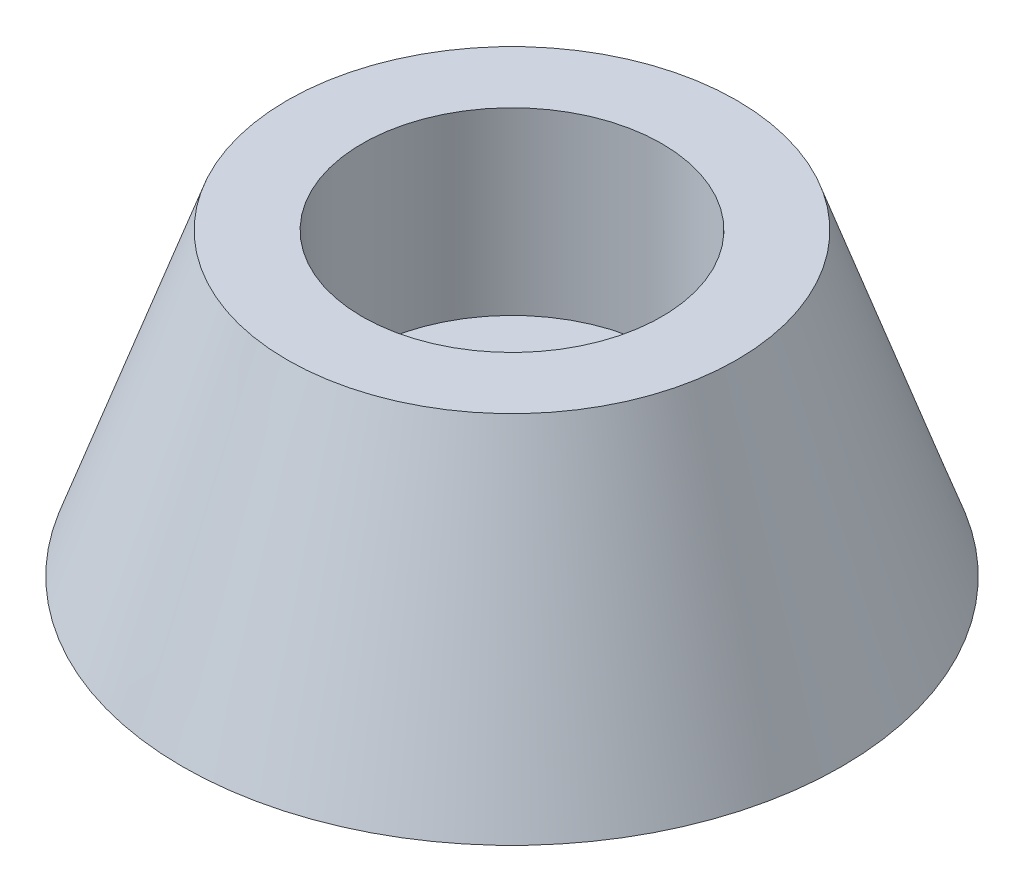
SolidWorks part; units mm, degrees
ref_plane "Спереди" through (0, 0, 0) normal (0, 0, 1) x (1, 0, 0)
ref_plane "Сверху" through (0, 0, 0) normal (0, 1, 0) x (1, 0, 0)
ref_plane "Справа" through (0, 0, 0) normal (1, 0, 0) x (0, 0, -1)
other "Configuration Table"
sketch "Эскиз2" plane through (0, 0, 0) normal (0, 0, 1) x (1, 0, 0)
  line L0 (0, 4.367) -> (-7.5, 4.367)
  line L1 (-7.5, 4.367) -> (-11, -5.633)
  line L2 (-11, -5.633) -> (0, -5.633)
  line L3 (0, -5.633) -> (0, 4.367)
  line L4 (0, -1000.3741) -> (0, 48999.6259) construction
  dimension "D1" = 7.5
  dimension "D2" = 11
  dimension "D3" = 10
revolve "Повернуть1" add sketch "Эскиз2" angle 360 about L3
sketch "Эскиз3" plane through (0, 4.367, 0) normal (0, 1, 0) x (1, 0, 0)
  circle A0 centre (0, 0) radius 2.25
extrude "Вырез-Вытянуть1" cut sketch "Эскиз3" against normal blind 10
sketch "Эскиз4" plane through (0, 4.367, 0) normal (0, 1, 0) x (1, 0, 0)
  circle A0 centre (0, 0) radius 5
extrude "Вырез-Вытянуть2" cut sketch "Эскиз4" against normal blind 6
sketch "Эскиз7" plane through (0, 0, 0) normal (0, 0, 1) x (1, 0, 0)
  line L0 (-11.9283, 0) -> (12.3915, 0) construction
  text T0 "Димон" font "Times New Roman" height 4
